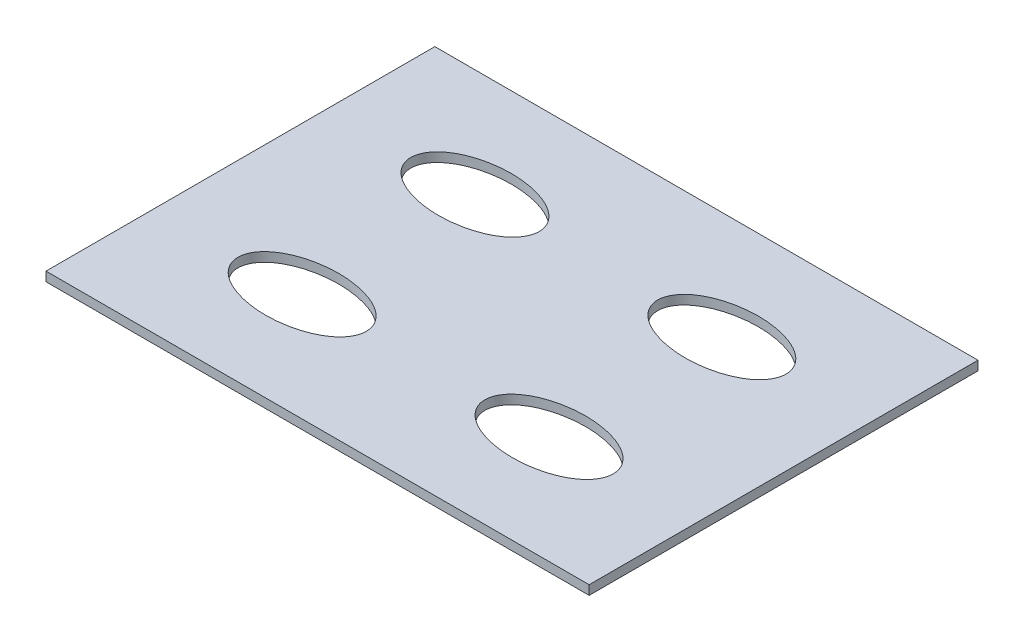
SolidWorks part; units mm, degrees
ref_plane "Front Plane" through (0, 0, 0) normal (0, 0, 1) x (1, 0, 0)
ref_plane "Top Plane" through (0, 0, 0) normal (0, 1, 0) x (1, 0, 0)
ref_plane "Right Plane" through (0, 0, 0) normal (1, 0, 0) x (0, 0, -1)
sketch "Sketch1" plane through (0, 0, 0) normal (0, 1, 0) x (1, 0, 0)
  line L0 (22, -15.75) -> (22, 15.75)
  line L1 (-22, -15.75) -> (22, -15.75)
  line L2 (-22, 15.75) -> (-22, -15.75)
  line L3 (22, 15.75) -> (-22, 15.75)
  spline S1 degree 3 poles (-14.9005, -5.785) (-15.3497, -7) (-14.9005, -8.215) (-13.3307, -9.4966) (-10, -10.2523) (-6.6693, -9.4966) (-5.0995, -8.215) (-4.6503, -7) (-5.0995, -5.785) (-6.6693, -4.5034) (-10, -3.7477) (-13.3307, -4.5034) (-14.9005, -5.785) (-15.3497, -7) (-14.9005, -8.215) knots -1.570796 -0.785398 -0.392699 0 0.392699 0.785398 1.570796 2.356194 2.748894 3.141593 3.534292 3.926991 4.712389 5.497787 5.890486 6.283185 6.675884 7.068583 7.853982 only from (-15.2, -7) to (-15.2, -7)
  spline S3 degree 3 poles (5.0995, -5.785) (4.6503, -7) (5.0995, -8.215) (6.6693, -9.4966) (10, -10.2523) (13.3307, -9.4966) (14.9005, -8.215) (15.3497, -7) (14.9005, -5.785) (13.3307, -4.5034) (10, -3.7477) (6.6693, -4.5034) (5.0995, -5.785) (4.6503, -7) (5.0995, -8.215) knots -1.570796 -0.785398 -0.392699 0 0.392699 0.785398 1.570796 2.356194 2.748894 3.141593 3.534292 3.926991 4.712389 5.497787 5.890486 6.283185 6.675884 7.068583 7.853982 only from (4.8, -7) to (4.8, -7)
  spline S5 degree 3 poles (5.0995, 8.215) (4.6503, 7) (5.0995, 5.785) (6.6693, 4.5034) (10, 3.7477) (13.3307, 4.5034) (14.9005, 5.785) (15.3497, 7) (14.9005, 8.215) (13.3307, 9.4966) (10, 10.2523) (6.6693, 9.4966) (5.0995, 8.215) (4.6503, 7) (5.0995, 5.785) knots -1.570796 -0.785398 -0.392699 0 0.392699 0.785398 1.570796 2.356194 2.748894 3.141593 3.534292 3.926991 4.712389 5.497787 5.890486 6.283185 6.675884 7.068583 7.853982 only from (4.8, 7) to (4.8, 7)
  spline S7 degree 3 poles (-14.9005, 8.215) (-15.3497, 7) (-14.9005, 5.785) (-13.3307, 4.5034) (-10, 3.7477) (-6.6693, 4.5034) (-5.0995, 5.785) (-4.6503, 7) (-5.0995, 8.215) (-6.6693, 9.4966) (-10, 10.2523) (-13.3307, 9.4966) (-14.9005, 8.215) (-15.3497, 7) (-14.9005, 5.785) knots -1.570796 -0.785398 -0.392699 0 0.392699 0.785398 1.570796 2.356194 2.748894 3.141593 3.534292 3.926991 4.712389 5.497787 5.890486 6.283185 6.675884 7.068583 7.853982 only from (-15.2, 7) to (-15.2, 7)
extrude "Boss-Extrude1" add sketch "Sketch1" along normal blind 0.75
